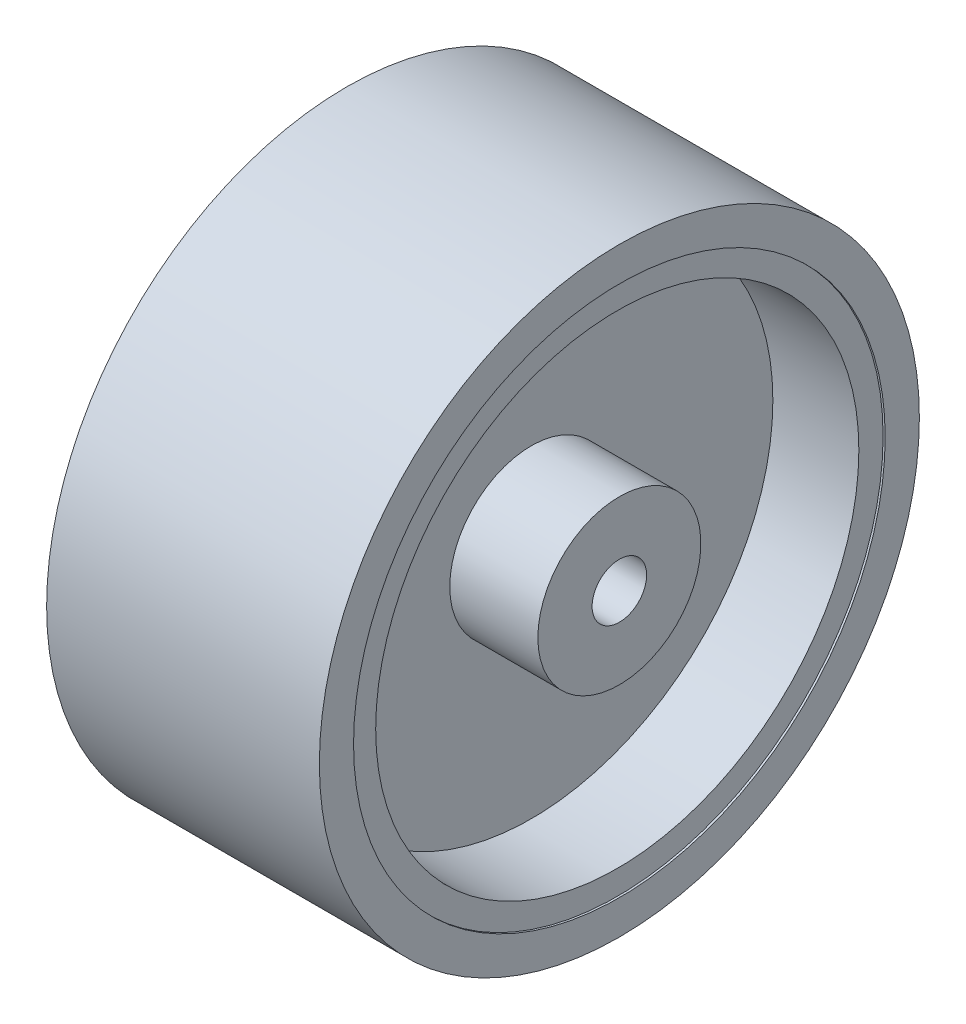
SolidWorks part; units mm, degrees
ref_plane "Front Plane" through (0, 0, 0) normal (0, 0, 1) x (1, 0, 0)
ref_plane "Top Plane" through (0, 0, 0) normal (0, 1, 0) x (1, 0, 0)
ref_plane "Right Plane" through (0, 0, 0) normal (1, 0, 0) x (0, 0, -1)
sketch "Sketch1" plane through (0, 0, 0) normal (0, 0, 1) x (1, 0, 0)
  line L0 (0, -30.9626) -> (0, 30.9626) construction
  line L1 (-44.6045, 0) -> (44.6045, 0) construction
  line L2 (-12.5, 27.5) -> (12.5, 27.5)
  line L3 (12.5, 27.5) -> (12.5, 24.3663)
  line L4 (12.5, 24.3663) -> (12.3076, 24.3663)
  line L5 (12.3076, 24.3663) -> (12.3076, 22.1448)
  line L6 (12.3076, 22.1448) -> (4.4256, 22.1448)
  line L7 (4.4256, 22.1448) -> (4.4256, 7.4715)
  line L8 (4.4256, 7.4715) -> (12.5, 7.4715)
  line L9 (12.5, 7.4715) -> (12.5, 2.5)
  line L10 (-12.5, 7.4715) -> (-12.5, 2.5)
  line L11 (-4.4256, 7.4715) -> (-12.5, 7.4715)
  line L12 (-4.4256, 22.1448) -> (-4.4256, 7.4715)
  line L13 (-12.3076, 22.1448) -> (-4.4256, 22.1448)
  line L14 (-12.3076, 24.3663) -> (-12.3076, 22.1448)
  line L15 (-12.5, 24.3663) -> (-12.3076, 24.3663)
  line L16 (-12.5, 27.5) -> (-12.5, 24.3663)
  line L18 (-12.5, 2.5) -> (12.5, 2.5)
  point P4 (0, 0)
  point P8 (0, 0)
  point P17 (-20.6247, 7.4715)
  point P24 (0, 27.5)
  dimension "D1" = 27.5
  dimension "D2" = 12.5
  dimension "D3" = 25
revolve "Revolve1" add sketch "Sketch1" angle 360 about L1
ref_plane "Plane1" through (0, 0, 0) normal (-1, 0, 0) x (0, 0, 1)
